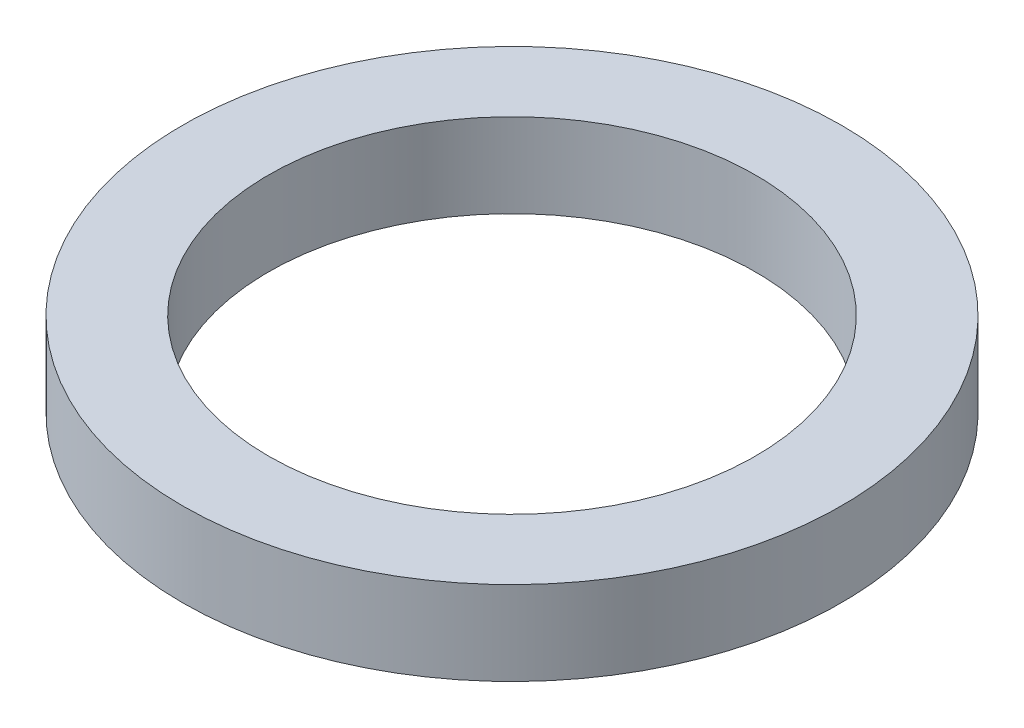
SolidWorks part; units mm, degrees
material "Rubber"
ref_plane "Front Plane" through (0, 0, 0) normal (0, 0, 1) x (1, 0, 0)
ref_plane "Top Plane" through (0, 0, 0) normal (0, 1, 0) x (1, 0, 0)
ref_plane "Right Plane" through (0, 0, 0) normal (1, 0, 0) x (0, 0, -1)
other "Configuration Table"
sketch "Sketch1" plane through (0, 0, 0) normal (0, 1, 0) x (1, 0, 0)
  circle A0 centre (0, 0) radius 5.8
  circle A1 centre (0, 0) radius 7.85
  dimension "D1" = 11.6
  dimension "D2" = 15.7
extrude "O_Ring" add sketch "Sketch1" along normal blind 2 from offset 1
equation "\"Jar_OD\"= 90  'ASSUMED - Part G fallback - jar outer diameter"
equation "\"Jar_H\"= 120  'ASSUMED - Part G fallback - jar height"
equation "\"Pump_L\"= 45  'ASSUMED - Part G fallback"
equation "\"Pump_W\"= 24  'ASSUMED - Part G fallback"
equation "\"Pump_H\"= 33  'ASSUMED - Part G fallback"
equation "\"Pump_Outlet_OD\"= 7.5  'ASSUMED - Part G fallback"
equation "\"Tube_OD\"= 8  'ASSUMED - Part G fallback"
equation "\"Tube_ID\"= 6  'ASSUMED - Part G fallback"
equation "\"TDS_Body_Dia\"= 12  'ASSUMED - Part G fallback"
equation "\"TDS_Wet_Len\"= 45  'ASSUMED - Part G fallback - length in water"
equation "\"DS_Tube_Dia\"= 6  'ASSUMED - Part G fallback"
equation "\"DS_Tube_Len\"= 50  'ASSUMED - Part G fallback"
equation "\"ORP_Body_Dia\"= 12  'ASSUMED - Part G fallback"
equation "\"ORP_Body_Len\"= 150  'ASSUMED - Part G fallback"
equation "\"ORP_Cap_Dia\"= 16  'ASSUMED - Part G fallback"
equation "\"Turb_W\"= 33  'ASSUMED - Part G fallback - head width"
equation "\"Turb_D\"= 28  'ASSUMED - Part G fallback - head depth"
equation "\"Turb_H\"= 30  'ASSUMED - Part G fallback - head height"
equation "\"Turb_Slot_W\"= 10  'ASSUMED - Part G fallback - slot width"
equation "\"Flow_L\"= 62  'ASSUMED - Part G fallback YF-S201"
equation "\"Flow_W\"= 36  'ASSUMED - Part G fallback"
equation "\"Flow_H\"= 35  'ASSUMED - Part G fallback"
equation "\"Thread_G12_OD\"= 20.955  'ASSUMED - Part G fallback thread G1/2 (major diameter)"
equation "\"Valve_L\"= 75  'ASSUMED - Part G fallback"
equation "\"Valve_W\"= 45  'ASSUMED - Part G fallback"
equation "\"Valve_H\"= 60  'ASSUMED - Part G fallback"
equation "\"Tee_L\"= 40  'ASSUMED - Part G fallback - overall length"
equation "\"Tee_Branch_L\"= 25  'ASSUMED - Part G fallback"
equation "\"Tee_OD\"= 12  'ASSUMED - Part G fallback"
equation "\"Cuv_W\"= 12.5  'ASSUMED - old R3 cuvette (station suppressed in SS4)"
equation "\"Cuv_D\"= 12.5  'ASSUMED - old R3 cuvette (station suppressed in SS4)"
equation "\"Cuv_H\"= 45  'ASSUMED - old R3 cuvette (station suppressed in SS4)"
equation "\"LED_Board_L\"= 20  'ASSUMED - Part G fallback"
equation "\"LED_Board_W\"= 20  'ASSUMED - Part G fallback - LED at centre"
equation "\"GUVA_L\"= 20  'ASSUMED - Part G fallback"
equation "\"GUVA_W\"= 12  'ASSUMED - Part G fallback - sensor at centre"
equation "\"Reed_L\"= 27  'ASSUMED - Part G fallback MC-38 half"
equation "\"Reed_W\"= 14  'ASSUMED - Part G fallback"
equation "\"Reed_H\"= 8  'ASSUMED - Part G fallback"
equation "\"ESP_L\"= 51  'ASSUMED - Part G fallback"
equation "\"ESP_W\"= 28  'ASSUMED - Part G fallback"
equation "\"TFT_L\"= 58  'ASSUMED - Part G fallback - board"
equation "\"TFT_W\"= 35  'ASSUMED - Part G fallback - board"
equation "\"TFT_Win_L\"= 35  'ASSUMED - Part G fallback - visible window"
equation "\"TFT_Win_W\"= 28  'ASSUMED - Part G fallback - visible window"
equation "\"Relay_L\"= 50  'ASSUMED - Part G fallback"
equation "\"Relay_W\"= 26  'ASSUMED - Part G fallback"
equation "\"Relay_H\"= 19  'ASSUMED - Part G fallback"
equation "\"Mosfet_L\"= 34  'ASSUMED - Part G fallback"
equation "\"Mosfet_W\"= 17  'ASSUMED - Part G fallback"
equation "\"Mosfet_H\"= 12  'ASSUMED - Part G fallback"
equation "\"TDS_Board_L\"= 42  'ASSUMED - Part G fallback"
equation "\"TDS_Board_W\"= 32  'ASSUMED - Part G fallback"
equation "\"Turb_Board_L\"= 38  'ASSUMED - Part G fallback"
equation "\"Turb_Board_W\"= 28  'ASSUMED - Part G fallback"
equation "\"BNC_Thread_Dia\"= 9.5  'ASSUMED - Part G fallback"
equation "\"Plate_L\"= 420  'ASSUMED - Part G fallback"
equation "\"Plate_W\"= 297  'ASSUMED - Part G fallback"
equation "\"Plate_T\"= 6  'ASSUMED - Part G fallback"
equation "\"Probe_Clr\"= 0.3  'DESIGN VALUE - Part C rule 3 - printed probe hole = diameter + 0.3"
equation "\"Cuv_Clr\"= 0.2  'DESIGN VALUE - Part C rule 3 - cuvette pocket = size + 0.2"
equation "\"Label_H\"= 0.6  'DESIGN VALUE - Part D - raised label height"
equation "\"Booster_L\"= 150  'ASSUMED - Part G fallback - booster pump"
equation "\"Booster_W\"= 95  'ASSUMED - Part G fallback"
equation "\"Booster_H\"= 100  'ASSUMED - Part G fallback"
equation "\"PTube_OD\"= 6.35  'ASSUMED - Part G fallback - product tube 1/4 inch"
equation "\"Qz_Out\"= 12  'ASSUMED - Part G fallback - quartz channel outside square"
equation "\"Qz_Path\"= 10  'ASSUMED - Part G fallback - quartz channel inside light path"
equation "\"Qz_L\"= 40  'ASSUMED - Part G fallback - quartz channel length"
equation "\"LED860_Dia\"= 5  'ASSUMED - Part G fallback - 860 nm LED"
equation "\"BPW_L\"= 5.4  'ASSUMED - Part G fallback - BPW34"
equation "\"BPW_W\"= 4.3  'ASSUMED - Part G fallback - BPW34"
equation "\"Cart_Dia\"= 50  'ASSUMED - Part G fallback - sediment and pre-carbon cartridges"
equation "\"Cart_L\"= 255  'ASSUMED - Part G fallback"
equation "\"UF_Dia\"= 50  'ASSUMED - Part G fallback - UF cartridge"
equation "\"UF_L\"= 260  'ASSUMED - Part G fallback"
equation "\"RO_Dia\"= 62  'ASSUMED - Part G fallback - RO membrane housing"
equation "\"RO_L\"= 300  'ASSUMED - Part G fallback"
equation "\"UVC_Dia\"= 40  'ASSUMED - Part G fallback - UV-C chamber"
equation "\"UVC_L\"= 300  'ASSUMED - Part G fallback"
equation "\"Tank_W\"= 260  'ASSUMED - Part G fallback - storage tank"
equation "\"Tank_D\"= 160  'ASSUMED - Part G fallback"
equation "\"Tank_H\"= 300  'ASSUMED - Part G fallback"
equation "\"Cab_W\"= 400  'ASSUMED - Part G fallback - purifier cabinet"
equation "\"Cab_D\"= 270  'ASSUMED - Part G fallback"
equation "\"Cab_H\"= 560  'ASSUMED - Part G fallback"
equation "\"ORP_Board_L\"= 40  'ASSUMED - Part G fallback - ORP buffer board"
equation "\"ORP_Board_W\"= 30  'ASSUMED - Part G fallback"
equation "\"Opt_Board_L\"= 50  'ASSUMED - Part G fallback - optical front-end board"
equation "\"Opt_Board_W\"= 40  'ASSUMED - Part G fallback"
equation "\"Buck_L\"= 43  'ASSUMED - Part G fallback - 12 V to 5 V buck module"
equation "\"Buck_W\"= 21  'ASSUMED - Part G fallback"
equation "\"Buck_H\"= 14  'ASSUMED - Part G fallback"
equation "\"BB_L\"= 165  'ASSUMED - Part G fallback - breadboard (As_Built_R3 only)"
equation "\"BB_W\"= 55  'ASSUMED - Part G fallback"
equation "\"BB_H\"= 10  'ASSUMED - Part G fallback"
